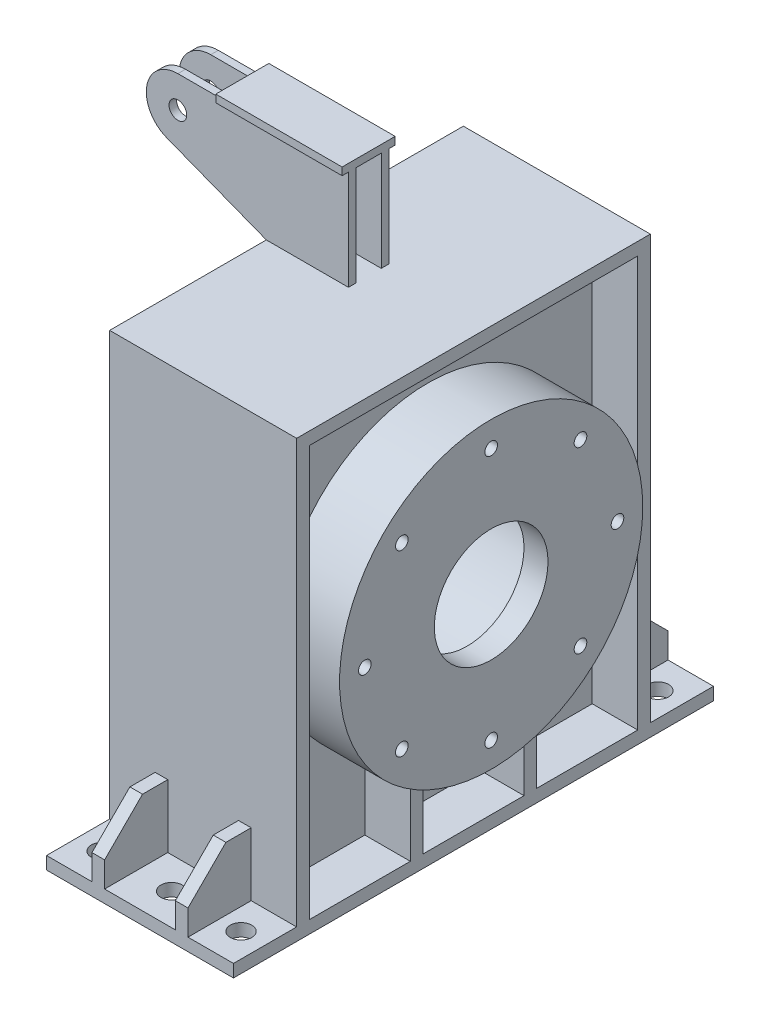
SolidWorks part; units mm, degrees
ref_plane "前视基准面" through (0, 0, 0) normal (0, 0, 1) x (1, 0, 0)
ref_plane "上视基准面" through (0, 0, 0) normal (0, 1, 0) x (1, 0, 0)
ref_plane "右视基准面" through (0, 0, 0) normal (1, 0, 0) x (0, 0, -1)
sketch "草图1" plane through (0, 0, 0) normal (0, 1, 0) x (1, 0, 0)
  line L1 (0, 0) -> (100, 0)
  line L2 (0, 0) -> (0, 42)
  line L3 (0, 42) -> (100, 42)
  line L4 (100, 0) -> (100, 42)
  dimension "D1" = 100
  dimension "D2" = 42
extrude "凸台-拉伸1" add sketch "草图1" along normal blind 6
sketch "草图2" plane through (0, 0, 0) normal (0, 1, 0) x (1, 0, 0)
  line L0 (100, 0) -> (100, 42) construction
  line L1 (-100, 37) -> (100, 37)
  line L2 (-100, 37) -> (-100, 31)
  line L3 (-100, 31) -> (100, 31)
  line L4 (100, 37) -> (100, 31)
  line L5 (100, 42) -> (0, 42) construction
  line L6 (-100, 11) -> (100, 11)
  line L7 (-100, 11) -> (-100, 5)
  line L8 (-100, 5) -> (100, 5)
  line L9 (100, 11) -> (100, 5)
  line L10 (0, 0) -> (100, 0) construction
  dimension "D1" = 5
  dimension "D2" = 5
  dimension "D3" = 6
  dimension "D4" = 6
  dimension "D5" = 200
  dimension "D6" = 200
extrude "凸台-拉伸2" add sketch "草图2" against normal blind 79
sketch "草图3" plane through (0, 0, -5) normal (0, 0, 1) x (1, 0, 0)
  line L0 (-100, 0) -> (0, 0) construction
  line L1 (100, -79) -> (100, 0) construction
  line L2 (-44.0493, -48.3047) -> (35, -79)
  line L3 (-100, -79) -> (100, -79) construction
  line L4 (35, -79) -> (-100, -79)
  line L5 (-100, -79) -> (-100, 0)
  line L6 (-100, 0) -> (-35, 0)
  circle A0 centre (-35, -25) radius 7
  arc A1 (-35, 0) -> (-44.0493, -48.3047) centre (-35, -25) ccw
  dimension "D3" = 14
  dimension "D4" = 25
  dimension "D1" = 25
  dimension "D2" = 135
  dimension "D5" = 65
extrude "切除-拉伸1" cut sketch "草图3" against normal through all
sketch "草图4" plane through (0, -79, 0) normal (0, -1, 0) x (-1, 0, 0)
  line L0 (-960.1686, 21) -> (49039.8314, 21) construction
  line L1 (-100, 11) -> (0, 11) construction
  line L2 (0, 31) -> (-100, 31) construction
  line L3 (-35, 5) -> (-35, 11) construction
  line L4 (-35, -119) -> (-183, -119)
  line L5 (-35, -119) -> (-35, 161)
  line L6 (-35, 161) -> (-183, 161)
  line L7 (-183, -119) -> (-183, 161)
  dimension "D1" = 280
  dimension "D2" = 148
extrude "凸台-拉伸3" add sketch "草图4" along normal blind 10
sketch "草图6" plane through (0, -89, 0) normal (0, -1, 0) x (-1, 0, 0)
  line L0 (-183, 161) -> (-183, -119) construction
  line L1 (-35, -119) -> (-183, -119)
  line L2 (-35, -119) -> (-35, -109)
  line L3 (-35, -109) -> (-183, -109)
  line L4 (-183, -119) -> (-183, -109)
  line L5 (-35, -119) -> (-35, 161) construction
  line L6 (-183, 161) -> (-35, 161)
  line L7 (-183, 161) -> (-183, 151)
  line L8 (-183, 151) -> (-35, 151)
  line L9 (-35, 161) -> (-35, 151)
  dimension "D1" = 10
  dimension "D2" = 10
extrude "凸台-拉伸4" add sketch "草图6" along normal blind 325
sketch "草图7" plane through (0, -414, 0) normal (0, -1, 0) x (-1, 0, 0)
  line L0 (-1183, 21) -> (48817, 21) construction
  line L1 (-183, 151) -> (-183, -109) construction
  line L2 (-35, -109) -> (-35, 151) construction
  line L3 (-35, -169) -> (-183, -169)
  line L4 (-35, -169) -> (-35, 211)
  line L5 (-35, 211) -> (-183, 211)
  line L6 (-183, -169) -> (-183, 211)
  point P5 (-183, 21)
  dimension "D1" = 380
extrude "凸台-拉伸5" add sketch "草图7" along normal blind 10
sketch "草图8" plane through (0, -414, 0) normal (0, 1, 0) x (1, 0, 0)
  line L0 (35, 161) -> (183, 161) construction
  line L1 (71, 161) -> (81, 161)
  line L2 (71, 161) -> (71, 211)
  line L3 (71, 211) -> (81, 211)
  line L4 (81, 161) -> (81, 211)
  line L5 (183, -119) -> (35, -119) construction
  line L6 (137, 161) -> (147, 161)
  line L7 (137, 161) -> (137, 211)
  line L8 (137, 211) -> (147, 211)
  line L9 (147, 161) -> (147, 211)
  line L10 (71, -169) -> (81, -169)
  line L11 (71, -169) -> (71, -119)
  line L12 (71, -119) -> (81, -119)
  line L13 (81, -169) -> (81, -119)
  line L14 (35, -169) -> (35, -119) construction
  line L15 (137, -169) -> (147, -169)
  line L16 (137, -169) -> (137, -119)
  line L17 (137, -119) -> (147, -119)
  line L18 (147, -169) -> (147, -119)
  line L19 (183, -119) -> (183, -169) construction
  line L20 (183, -169) -> (35, -169) construction
  line L21 (35, 161) -> (35, 211) construction
  line L22 (183, 211) -> (183, 161) construction
  line L23 (35, 211) -> (183, 211) construction
  dimension "D1" = 10
  dimension "D2" = 10
  dimension "D3" = 36
  dimension "D4" = 36
  dimension "D5" = 10
  dimension "D6" = 10
  dimension "D7" = 36
  dimension "D8" = 36
extrude "凸台-拉伸6" add sketch "草图8" along normal blind 50
sketch "草图9" plane through (147, 0, 0) normal (1, 0, 0) x (0, 0, -1)
  line L0 (211, -364) -> (181, -364)
  line L1 (161, -364) -> (211, -364) construction
  line L2 (181, -364) -> (211, -394)
  line L3 (211, -364) -> (211, -414) construction
  line L4 (211, -394) -> (211, -364)
  line L5 (-169, -364) -> (-139, -364)
  line L6 (-169, -364) -> (-119, -364) construction
  line L7 (-169, -364) -> (-169, -414) construction
  line L8 (-139, -364) -> (-169, -394)
  line L9 (-169, -394) -> (-169, -364)
  dimension "D1" = 30
  dimension "D2" = 30
  dimension "D3" = 30
  dimension "D4" = 30
extrude "切除-拉伸2" cut sketch "草图9" against normal through all
sketch "草图10" plane through (147, 0, 0) normal (1, 0, 0) x (0, 0, -1)
  line L0 (151, -414) -> (-109, -414) construction
  line L1 (-109, -89) -> (151, -89)
  line L2 (-109, -89) -> (-109, -414)
  line L3 (-109, -414) -> (151, -414)
  line L4 (151, -89) -> (151, -414)
  line L5 (21, -1414) -> (21, 48586) construction
  circle A0 centre (21, -249) radius 120
  point P12 (21, -414)
  dimension "D1" = 165
  dimension "D2" = 240
extrude "凸台-拉伸7" add sketch "草图10" against normal blind 10
pattern_linear "阵列(线性)1" count 2 spacing 66 along (-1, 0, 0) of "凸台-拉伸7"
sketch "草图12" plane through (35, 0, 0) normal (-1, 0, 0) x (0, 0, 1)
  circle A0 centre (-21, -249) radius 120
  circle A1 centre (-21, -249) radius 120 construction
  circle A2 centre (-21, -249) radius 80
  dimension "D1" = 160
extrude "凸台-拉伸9" add sketch "草图12" against normal blind 148 separate body
sketch "草图13" plane through (0, -414, 0) normal (0, 1, 0) x (1, 0, 0)
  line L0 (147, -109) -> (147, 151) construction
  line L1 (147, -19) -> (183, -19)
  line L2 (147, -19) -> (147, -29)
  line L3 (147, -29) -> (183, -29)
  line L4 (183, -19) -> (183, -29)
  line L5 (183, 151) -> (147, 151) construction
  line L6 (147, 61) -> (183, 61)
  line L7 (147, 61) -> (147, 71)
  line L8 (147, 71) -> (183, 71)
  line L9 (183, 61) -> (183, 71)
  line L10 (147, -109) -> (183, -109) construction
  line L11 (71, -109) -> (71, 151) construction
  line L12 (71, 71) -> (35, 71)
  line L13 (71, 71) -> (71, 61)
  line L14 (71, 61) -> (35, 61)
  line L15 (35, 71) -> (35, 61)
  line L16 (35, -109) -> (35, 151) construction
  line L17 (71, 151) -> (35, 151) construction
  line L18 (71, -19) -> (35, -19)
  line L19 (71, -19) -> (71, -29)
  line L20 (71, -29) -> (35, -29)
  line L21 (35, -19) -> (35, -29)
  line L22 (35, -109) -> (71, -109) construction
  dimension "D1" = 10
  dimension "D2" = 10
  dimension "D3" = 80
  dimension "D4" = 80
  dimension "D5" = 36
  dimension "D6" = 36
  dimension "D7" = 10
  dimension "D8" = 10
  dimension "D9" = 80
  dimension "D10" = 80
extrude "凸台-拉伸10" add sketch "草图13" along normal blind 50
sketch "草图14" plane through (183, 0, 0) normal (1, 0, 0) x (0, 0, -1)
  circle A0 centre (21, -249) radius 80
  circle A1 centre (21, -249) radius 80 construction
  circle A2 centre (21, -249) radius 65
  dimension "D1" = 130
extrude "凸台-拉伸11" add sketch "草图14" against normal blind 14
sketch "草图15" plane through (183, 0, 0) normal (1, 0, 0) x (0, 0, -1)
  circle A0 centre (21, -249) radius 45
  circle A1 centre (21, -249) radius 65
  circle A4 centre (21, -249) radius 120 construction
  dimension "D1" = 90
  dimension "D2" = 130
extrude "凸台-拉伸12" add sketch "草图15" against normal blind 5 separate body
sketch "草图17" plane through (183, 0, 0) normal (1, 0, 0) x (0, 0, -1)
  circle A0 centre (21, -249) radius 45
  circle A1 centre (21, -249) radius 120
  circle A4 centre (21, -249) radius 120 construction
  circle A5 centre (21, -249) radius 45 construction
  dimension "D2" = 240
extrude "凸台-拉伸13" add sketch "草图17" along normal blind 14
sketch "草图18" plane through (35, 0, 0) normal (-1, 0, 0) x (0, 0, 1)
  circle A0 centre (-21, -249) radius 65
  circle A1 centre (-21, -249) radius 80
  circle A2 centre (-21, -249) radius 80 construction
  dimension "D1" = 130
extrude "凸台-拉伸14" add sketch "草图18" against normal blind 14
sketch "草图19" plane through (35, 0, 0) normal (-1, 0, 0) x (0, 0, 1)
  circle A0 centre (-21, -249) radius 25
  circle A1 centre (-21, -249) radius 65
  circle A2 centre (-21, -249) radius 65 construction
  dimension "D1" = 50
extrude "凸台-拉伸15" add sketch "草图19" against normal blind 5 separate body
sketch "草图20" plane through (35, 0, 0) normal (-1, 0, 0) x (0, 0, 1)
  circle A0 centre (-21, -249) radius 25
  circle A1 centre (-21, -249) radius 120
  circle A2 centre (-21, -249) radius 120 construction
  circle A3 centre (-21, -249) radius 25 construction
extrude "凸台-拉伸16" add sketch "草图20" along normal blind 14
sketch "草图27" plane through (0, -424, 0) normal (0, -1, 0) x (-1, 0, 0)
  line L0 (-1183, 21) -> (48817, 21) construction
  line L1 (-183, 211) -> (-183, -169) construction
  line L2 (-1132.1732, -144) -> (48867.8268, -144) construction
  line L4 (-1142.1544, 186) -> (48857.8456, 186) construction
  line L5 (-109, -1169) -> (-109, 48831) construction
  line L6 (-183, -169) -> (-35, -169) construction
  line L7 (-54, -1144) -> (-54, 48856) construction
  line L8 (-164, -1144) -> (-164, 48856) construction
  circle A0 centre (-109, -144) radius 8.5
  circle A1 centre (-164, -144) radius 8.5
  circle A2 centre (-54, -144) radius 8.5
  circle A3 centre (-54, 186) radius 8.5
  circle A4 centre (-109, 186) radius 8.5
  circle A5 centre (-164, 186) radius 8.5
  circle A6 centre (-54, 111) radius 8.5
  circle A7 centre (-54, -69) radius 8.5
  circle A8 centre (-54, 21) radius 8.5
  point P5 (-183, 21)
  point P17 (-109, -169)
  dimension "D4" = 17
  dimension "D1" = 165
  dimension "D2" = 165
  dimension "D3" = 110
  dimension "D5" = 90
  dimension "D6" = 90
extrude "切除-拉伸4" cut sketch "草图27" against normal blind 10
sketch "草图28" plane through (197, 0, 0) normal (1, 0, 0) x (0, 0, -1)
  line L0 (21, -1249) -> (21, 48751) construction
  line L1 (-979, -249) -> (49021, -249) construction
  circle A0 centre (21, -149) radius 5
  dimension "D1" = 10
  dimension "D2" = 100
extrude "切除-拉伸5" cut sketch "草图28" against normal blind 25
sketch "草图29" plane through (21, 0, 0) normal (-1, 0, 0) x (0, 0, 1)
  line L0 (-1021, -249) -> (48979, -249) construction
  line L1 (-21, -1249) -> (-21, 48751) construction
  circle A0 centre (-21, -149) radius 5
  dimension "D1" = 10
  dimension "D2" = 100
extrude "切除-拉伸6" cut sketch "草图29" against normal blind 25
pattern_circular "阵列(圆周)2" count 8 over 360 about axis through (0, -249, -21) along (1, 0, 0) of "切除-拉伸5", "切除-拉伸6"
